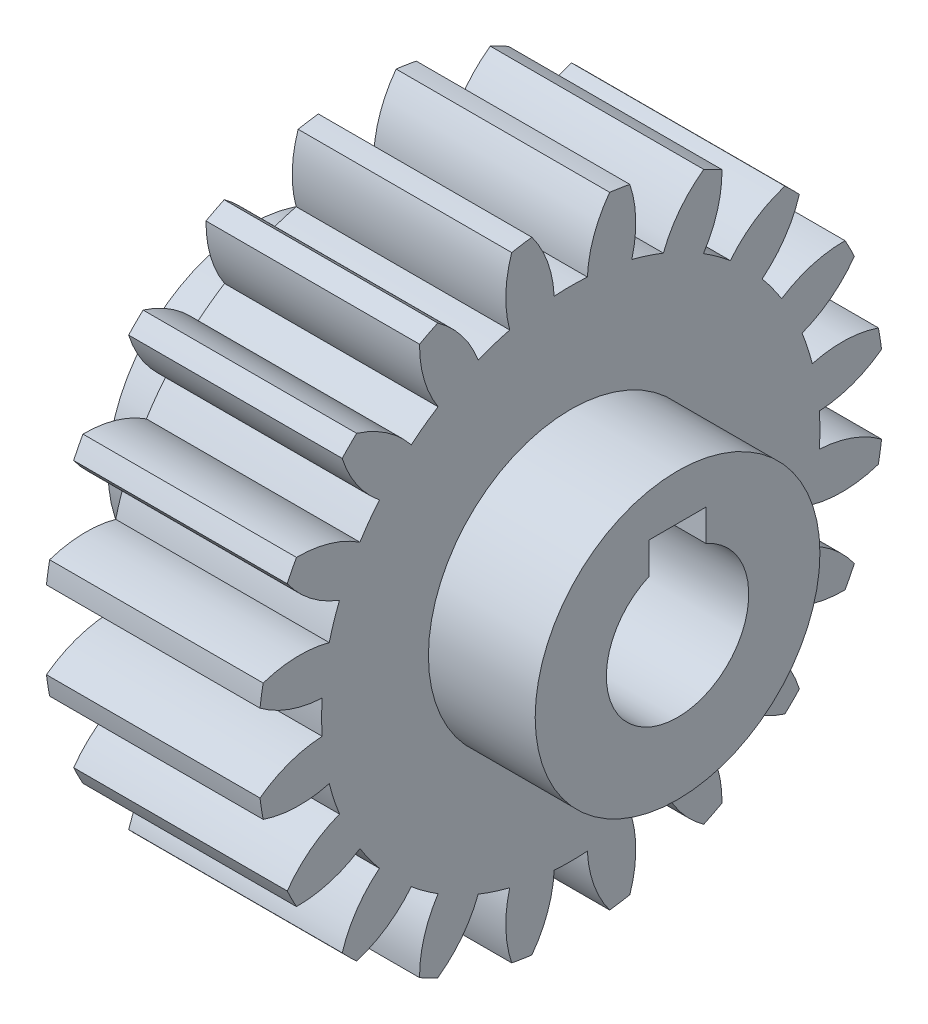
SolidWorks part; units mm, degrees
ref_plane "Plane1" through (0, 0, 0) normal (0, 0, 1) x (1, 0, 0)
ref_plane "Plane2" through (0, 0, 0) normal (0, 1, 0) x (1, 0, 0)
ref_plane "Plane3" through (0, 0, 0) normal (1, 0, 0) x (0, 0, -1)
sketch "HoldingSke" plane through (0, 0, 0) normal (0, 1, 0) x (1, 0, 0)
  line L0 (0, 0) -> (0.4698, -0.171)
  line L1 (-15, 0) -> (100, 0) construction
  line L2 (0, 0) -> (-2.1039, 2.3779)
  line L3 (0, 0) -> (-11.863, 4.5341)
  line L4 (0, 0) -> (8.1152, 2.9537)
  line L5 (0, 0) -> (-28.1086, -10.4837)
  line L6 (0, 0) -> (-12.4344, -8.3896)
  line L7 (-2.1039, 2.3779) -> (4.3536, 31.6747)
  line L8 (-76.2, 54.61) -> (-74.4, 54.61)
  line L9 (-67.7845, 28.3722) -> (-49.3413, 33.142)
  line L10 (-76.2, 71.12) -> (104.1128, 71.12)
  line L11 (0, 0) -> (-15, 0)
  line L12 (-76.2, 101.6) -> (-76.133, 101.6)
  line L13 (24.9733, 27.94) -> (52.9518, 28.4284)
  line L14 (24.9733, 27.94) -> (24.9743, 27.94)
  line L15 (24.9733, 27.94) -> (100.4006, 29.5858)
  line L16 (-63.627, -2) -> (-12.827, -2)
  circle A0 centre (0, 0) radius 5
  circle A1 centre (0, 0) radius 10
  circle A2 centre (0, 0) radius 10
  circle A3 centre (0, 0) radius 5
  dimension "MHD" = 20
  dimension "Hub_dia" = 20
  dimension "Bore" = 10
  dimension "MBD" = 10
  dimension "Num_teeth" = 20
  dimension "Pitch" = 0.5
  dimension "Overall_len" = 30
  dimension "Show_teeth" = 20
  dimension "Thickness" = 15
  dimension "OAL" = 30.0001
  dimension "T_dim" = 1.8
  dimension "Ap" = 14.5
  dimension "H" = 19.05
  dimension "Pitch_radius" = 180.3128
  dimension "Width" = 15
  dimension "Backlash" = 0.067
  dimension "Addendum_fac" = 1
  dimension "Dedendum_fac" = 1.25
  dimension "Clearance_fac" = 0.25
  dimension "Dedendum_add" = 0.001
  dimension "Module" = 2
sketch "BasProSke" plane through (0, 0, 0) normal (0, 1, 0) x (1, 0, 0)
  line L0 (-10, 0) -> (60, 0) construction
  line L1 (0, 0) -> (0, 22)
  line L2 (0, 0) -> (15, 0)
  line L3 (15, 0) -> (15, 22)
  line L4 (15, 22) -> (0, 22)
  dimension "Thickness" = 15
  dimension "Diameter" = 44
revolve "Base-Revolve" add sketch "BasProSke" angle 360 about L0
sketch "TooCutSke" plane through (0, 0, 0) normal (1, 0, 0) x (0, 0, -1)
  line L1 (0, 0) -> (0, 107) construction
  line L2 (0, 0) -> (-1.6864, 19.9288) construction
  line L3 (0, 0) -> (-6.2409, 39.4033) construction
  line L4 (-1.6864, 19.9288) -> (-3.1204, 19.7016) construction
  arc A0 (1.165, 17.4602) -> (-1.165, 17.4602) centre (0, 0) ccw
  arc A1 (2.7485, 21.8532) -> (-2.7485, 21.8532) centre (0, 0) ccw
  circle A2 centre (0, 0) radius 20 construction
  circle A3 centre (0, 0) radius 19.363 construction
  arc A4 (-1.165, 17.4602) -> (-2.7485, 21.8532) centre (-9.1551, 17.0619) ccw
  arc A5 (2.7485, 21.8532) -> (1.165, 17.4602) centre (9.1551, 17.0619) ccw
  dimension "Root_dia" = 34.998
  dimension "Overcut_dia" = 44.0508
  dimension "Pitch_dia" = 40
  dimension "Base_dia" = 38.7259
  dimension "Flank_rad" = 8
  dimension "Half_ang" = 9
  dimension "Half_CT" = 1.4519
extrude "ToothCut" cut sketch "TooCutSke" along normal through all
fillet "Breaks" [suppressed] radius 0.04
fillet "RootFillets" [suppressed] radius 0.501
pattern_circular "TeethCuts" count 20 every 18 about axis through (-10, 0, 0) along (1, 0, 0) of "ToothCut", "RootFillets", "Breaks"
sketch "HubNeaOneSke" plane through (0, 0, 0) normal (-1, 0, 0) x (0, 0, 1)
  circle A0 centre (0, 0) radius 10
  dimension "Diameter" = 20
extrude "HubNearOne" [suppressed] add sketch "HubNeaOneSke" along normal blind 15.0001
sketch "HubNeaBotSke" plane through (0, 0, 0) normal (-1, 0, 0) x (0, 0, 1)
  circle A0 centre (0, 0) radius 10
  dimension "Diameter" = 20
extrude "HubNearBoth" add sketch "HubNeaBotSke" along normal blind 7.5
ref_plane "FarPln" through (15, 0, 0) normal (1, 0, 0) x (0, 0, -1)
sketch "HubFarSke" plane through (15, 0, 0) normal (1, 0, 0) x (0, 0, -1)
  circle A0 centre (0, 0) radius 10
  dimension "Diameter" = 20
extrude "HubFar" add sketch "HubFarSke" along normal blind 7.5
sketch "BorSke" plane through (0, 0, 0) normal (1, 0, 0) x (0, 0, -1)
  circle A0 centre (0, 0) radius 5
  dimension "Diameter" = 10
extrude "Bore" cut sketch "BorSke" along normal mid plane 60.0001
sketch "KeySke" plane through (0, 0, 0) normal (1, 0, 0) x (0, 0, -1)
  line L0 (-2, 0) -> (-2, 6.8)
  line L1 (-2, 6.8) -> (2, 6.8)
  line L2 (2, 6.8) -> (2, 0)
  line L3 (0, 0) -> (0, 34) construction
  line L4 (-2, 0) -> (2, 0)
  dimension "Offset" = 6.8
  dimension "Width" = 4
extrude "Keyway" cut sketch "KeySke" along normal mid plane 60.0001
pattern_circular "Keyway2" [suppressed] count 2 every 90 about axis through (-10, 0, 0) along (1, 0, 0)
equation "' \"Module@HoldingSke\" = 6.35"
equation "' \"Num_teeth@HoldingSke\" = 12"
equation "' \"Ap@HoldingSke\" =  20"
equation "' \"Ap@HoldingSke\" = 20"
equation "' \"Width@HoldingSke\" = 0.5 * 25.4"
equation "' \"Hub_dia@HoldingSke\"= 1 * 25.4"
equation "' \"Hub_dia@HoldingSke\" = 1 * 25.4"
equation "' \"Overall_len@HoldingSke\" = 1.0 * 25.4"
equation "' \"Bore@HoldingSke\" = 0.75 * 25.4"
equation "' \"T_dim@HoldingSke\" = 0.1 * 25.4"
equation "' \"Width@KeySke\" = 0.25 * 25.4"
equation "' \"Show_teeth@HoldingSke\" = 13"
equation "' \"Backlash@HoldingSke\" = 0.009 * 25.4"
equation "' \"Addendum_fac@HoldingSke\" = 1.0"
equation "' \"Dedendum_fac@HoldingSke\" = 1.25"
equation "' \"Dedendum_add@HoldingSke\" = 0.00005 * 25.4"
equation "' \"Clearance_fac@HoldingSke\" = 0.25"
equation "\"Pitch@HoldingSke\" = 1 / \"Module@HoldingSke\""
equation "\"Overcut_dia@TooCutSke\" = (\"Num_teeth@HoldingSke\" + 2 * \"Addendum_fac@HoldingSke\") / \"Pitch@HoldingSke\" + 0.002 * 25.4"
equation "\"Pitch_dia@TooCutSke\" = \"Num_teeth@HoldingSke\" / \"Pitch@HoldingSke\""
equation "\"Base_dia@TooCutSke\" = \"Num_teeth@HoldingSke\" / \"Pitch@HoldingSke\" * cos((\"Ap@HoldingSke\"  * 3.14159265 / 180))"
equation "\"Root_dia@TooCutSke\" = (\"Num_teeth@HoldingSke\" + 2) / \"Pitch@HoldingSke\" - 2 * (\"Addendum_fac@HoldingSke\" + \"Dedendum_fac@HoldingSke\") / \"Pitch@HoldingSke\" - \"Dedendum_add@HoldingSke\" * 2"
equation "\"Half_ang@TooCutSke\" = 180 / \"Num_teeth@HoldingSke\""
equation "\"Half_CT@TooCutSke\" = \"Num_teeth@HoldingSke\" / \"Pitch@HoldingSke\" * sin((3.14159265 / 2 / \"Num_teeth@HoldingSke\")) / 2 - 7 * \"Backlash@HoldingSke\" / 4"
equation "\"Flank_rad@TooCutSke\" = \"Num_teeth@HoldingSke\" / \"Pitch@HoldingSke\" / 5"
equation "\"Radius@RootFillets\" = \"Clearance_fac@HoldingSke\" / \"Pitch@HoldingSke\" + \"Dedendum_add@HoldingSke\""
equation "\"Break_rad@Breaks\" = 0.02 / \"Pitch@HoldingSke\""
equation "\"Thickness@HoldingSke\" = \"Width@HoldingSke\""
equation "\"OAL@HoldingSke\" = \"Thickness@HoldingSke\""
equation "\"MHD@HoldingSke\" = (\"Num_teeth@HoldingSke\" + 2) / \"Pitch@HoldingSke\" - 2 * (\"Addendum_fac@HoldingSke\" + \"Dedendum_fac@HoldingSke\")  / \"Pitch@HoldingSke\" - \"Dedendum_add@HoldingSke\" * 2"
equation "\"MBD@HoldingSke\" = (\"Num_teeth@HoldingSke\" + 2) / \"Pitch@HoldingSke\" - 2 * (\"Addendum_fac@HoldingSke\" + \"Dedendum_fac@HoldingSke\")  / \"Pitch@HoldingSke\" - \"Dedendum_add@HoldingSke\" * 2 - 0.002 * 25.4"
equation "\"MHD@HoldingSke\" = ((sgn( \"MHD@HoldingSke\" - \"Hub_dia@HoldingSke\" )-1)*( \"MHD@HoldingSke\" - \"Hub_dia@HoldingSke\" ))/-2+ \"Hub_dia@HoldingSke\""
equation "\"MBD@HoldingSke\" = ((sgn( \"MBD@HoldingSke\" - \"Bore@HoldingSke\" )-1)*( \"MBD@HoldingSke\" - \"Bore@HoldingSke\" ))/-2+ \"Bore@HoldingSke\""
equation "\"OAL@HoldingSke\" = ((sgn( \"OAL@HoldingSke\" - \"Overall_len@HoldingSke\" )+1)*( \"OAL@HoldingSke\" - \"Overall_len@HoldingSke\" ))/2 + \"Overall_len@HoldingSke\" + 0.000002 * 25.4"
equation "\"Num_teeth@TeethCuts\" = int( \"Show_teeth@HoldingSke\" ) + 1"
equation "\"Num_teeth@TeethCuts\" = ((sgn( \"Num_teeth@TeethCuts\" - \"Num_teeth@HoldingSke\" )-1)*( \"Num_teeth@TeethCuts\" - \"Num_teeth@HoldingSke\" ))/-2+ \"Num_teeth@HoldingSke\""
equation "\"Num_teeth@TeethCuts\" = ((sgn( \"Num_teeth@TeethCuts\" - 2.0)+1)*( \"Num_teeth@TeethCuts\" - 2.0))/2 +2.0"
equation "\"Angle@TeethCuts\" = 360.0 / \"Num_teeth@HoldingSke\""
equation "\"Diameter@BasProSke\" = (\"Num_teeth@HoldingSke\" + 2 * \"Addendum_fac@HoldingSke\") / \"Pitch@HoldingSke\""
equation "\"Thickness@BasProSke\"  = \"Thickness@HoldingSke\""
equation "' \"Fillet_rad@BasProSke\" =  \"Thickness@HoldingSke\" * 0.05"
equation "' \"Fillet_rad@BasProSke\" = \"Thickness@HoldingSke\" * 0.05"
equation "\"MHD@HoldingSke\" = ((sgn( \"MHD@HoldingSke\" - \"Root_dia@TooCutSke\" )-1)*( \"MHD@HoldingSke\" - \"Root_dia@TooCutSke\" ))/-2+ \"Root_dia@TooCutSke\""
equation "\"Diameter@HubNeaOneSke\" = \"MHD@HoldingSke\""
equation "\"Length@HubNearOne\" = \"OAL@HoldingSke\" - \"Thickness@BasProSke\""
equation "\"Diameter@HubNeaBotSke\" = \"MHD@HoldingSke\""
equation "\"Length@HubNearBoth\" = ( \"OAL@HoldingSke\" - \"Thickness@BasProSke\" ) / 2.0"
equation "\"Thickness@FarPln\" = \"Thickness@BasProSke\""
equation "\"Diameter@HubFarSke\" = \"MHD@HoldingSke\""
equation "\"Length@HubFar\" = ( \"OAL@HoldingSke\" - \"Thickness@BasProSke\" ) / 2.0"
equation "\"Diameter@BorSke\" = \"MBD@HoldingSke\""
equation "\"D1@Bore\" = \"OAL@HoldingSke\" * 2.0"
equation "\"D1@Keyway\" = \"OAL@HoldingSke\" * 2.0"
equation "\"Offset@KeySke\" = \"T_dim@HoldingSke\" + \"MBD@HoldingSke\" / 2.0"
